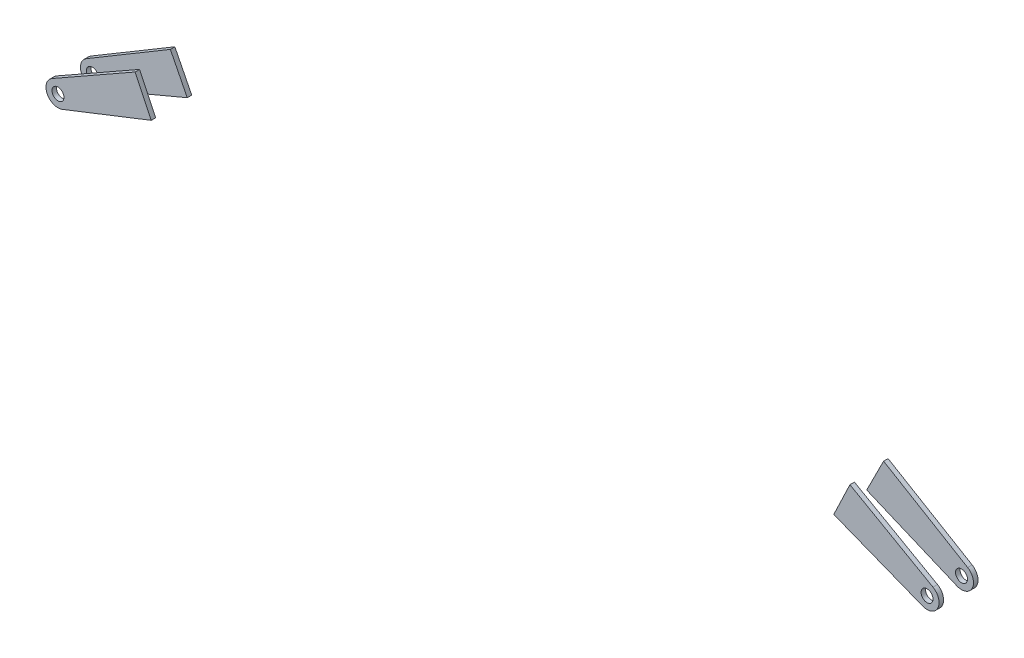
SolidWorks part; units mm, degrees
material "AISI 4130 Steel, normalized at 870C"
ref_plane "Front Plane" through (0, 0, 0) normal (0, 0, 1) x (1, 0, 0)
ref_plane "Top Plane" through (0, 0, 0) normal (0, 1, 0) x (1, 0, 0)
ref_plane "Right Plane" through (0, 0, 0) normal (1, 0, 0) x (0, 0, -1)
sketch3d "3DSketch1"
  line L0 (290, -1970, 165) -> (290, -1970, 175) construction
  line L1 (240, -1960, 350) -> (230, -1935, 95) construction
  line L2 (240, -1960, 350) -> (230, -1935, 95) construction
  line L3 (293.9509, -1963.0437, 175) -> (238.5243, -1931.5635, 175)
  line L4 (287.0729, -1977.4453, 175) -> (227.7503, -1954.1228, 175)
  line L5 (227.7503, -1954.1228, 175) -> (238.5243, -1931.5635, 175)
  circle A0 centre (290, -1970, 175) radius 4
  arc A1 (287.0729, -1977.4453, 175) -> (293.9509, -1963.0437, 175) centre (290, -1970, 175) ccw
  point P8 (290, -1970, 179)
  point P11 (290, -1970, 183)
  point P15 (233.1373, -1942.8431, 175)
  dimension "D1" = 8
  dimension "D2" = 4
  dimension "D3" = 25
extrude "Boss-Extrude-U" add sketch "3DSketch1" along a picked direction on the side against the normal blind 3 contours L3 L5 L4 A1 | A0
sketch3d "3DSketch2"
  line L6 (240, -1960, 350) -> (230, -1935, 95) construction
  line L7 (240, -1960, 350) -> (230, -1935, 95) construction
  line L8 (290, -1970, 165) -> (290, -1970, 155) construction
  line L9 (286.8961, -1977.3733, 155) -> (226.7173, -1952.0398, 155)
  line L10 (226.7173, -1952.0398, 155) -> (237.9886, -1929.7249, 155)
  line L11 (237.9886, -1929.7249, 155) -> (294.0924, -1963.126, 155)
  circle A4 centre (290, -1970, 155) radius 4
  arc A5 (286.8961, -1977.3733, 155) -> (294.0924, -1963.126, 155) centre (290, -1970, 155) ccw
  point P0 (290, -1970, 165)
  point P9 (290, -1970, 159)
  point P11 (290, -1970, 163)
  point P17 (232.3529, -1940.8824, 155)
  dimension "D1" = 8
  dimension "D2" = 4
  dimension "D3" = 25
extrude "Boss-Extrude-L" add sketch "3DSketch2" along a picked direction on the side against the normal blind 3 contours L11 A5 L9 L10 | A4
mirror "Mirror1" about plane through (0, 0, 0) normal (1, 0, 0) of bodies 107 106
